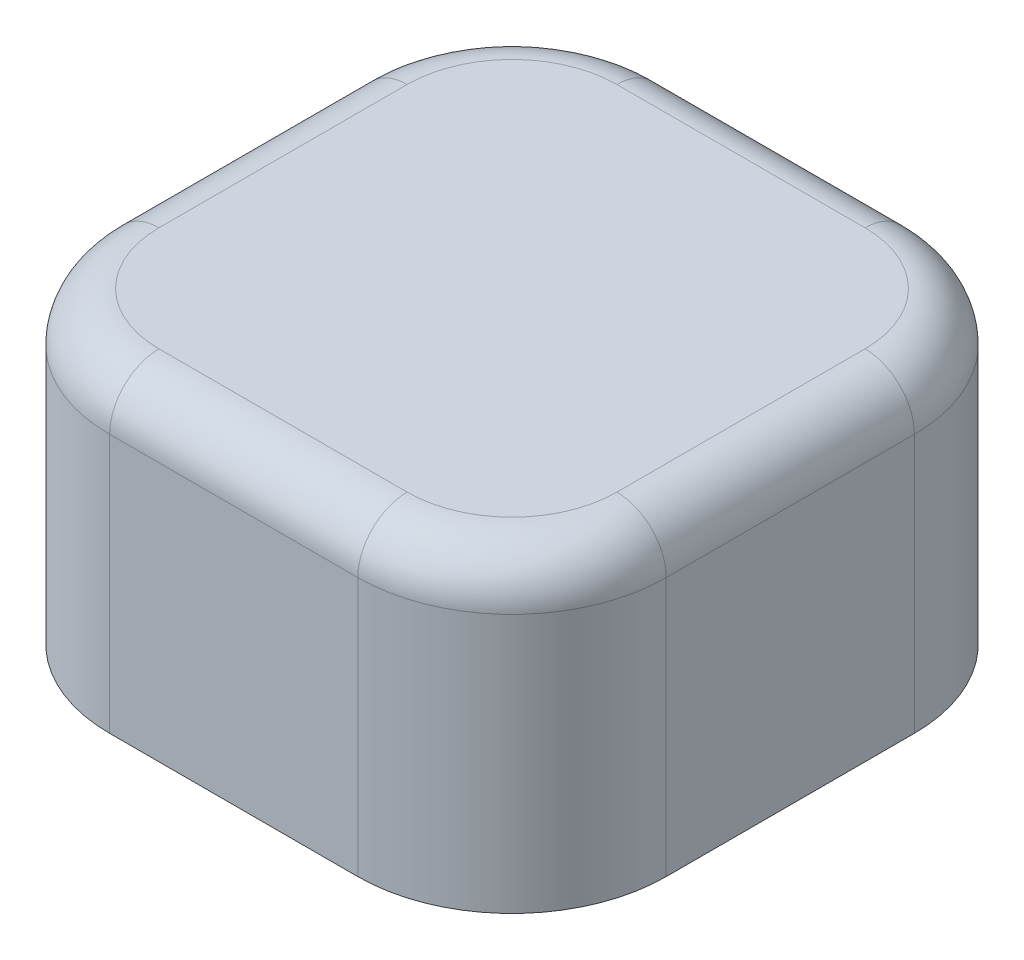
SolidWorks part; units mm, degrees
ref_plane "前视基准面" through (0, 0, 0) normal (0, 0, 1) x (1, 0, 0)
ref_plane "上视基准面" through (0, 0, 0) normal (0, 1, 0) x (1, 0, 0)
ref_plane "右视基准面" through (0, 0, 0) normal (1, 0, 0) x (0, 0, -1)
other "Configuration Table"
sketch "草图1" plane through (0, 0, 0) normal (0, 1, 0) x (1, 0, 0)
  line L0 (-2.2, 0) -> (2.2, 0) construction
  line L1 (0, 2.2) -> (0, -2.2) construction
  line L2 (2.2, 0.6) -> (2.2, -0.6)
  line L3 (-0.6, 2.2) -> (0.6, 2.2)
  line L4 (-2.2, -0.6) -> (-2.2, 0.6)
  line L5 (-0.6, -2.2) -> (0.6, -2.2)
  line L6 (-0.6, 2.2) -> (-0.6, 0.6)
  line L7 (-0.6, 0.6) -> (-2.2, 0.6)
  line L8 (-2.2, -0.6) -> (-0.6, -0.6)
  line L9 (-0.6, -0.6) -> (-0.6, -2.2)
  line L10 (0.6, -2.2) -> (0.6, -0.6)
  line L11 (0.6, -0.6) -> (2.2, -0.6)
  line L12 (2.2, 0.6) -> (0.6, 0.6)
  line L13 (0.6, 0.6) -> (0.6, 2.2)
  circle A0 centre (0, 0) radius 2.8
  point P4 (0, 0)
  point P7 (0, 0)
  point P10 (2.2, 0)
  point P13 (0, 2.2)
  point P16 (-2.2, 0)
  point P19 (0, -2.2)
  dimension "D7" = 5.6
  dimension "D1" = 4.4
  dimension "D2" = 4.4
  dimension "D3" = 1.2
  dimension "D4" = 1.2
  dimension "D5" = 1.2
  dimension "D6" = 1.2
extrude "凸台-拉伸1" add sketch "草图1" against normal blind 8
sketch "草图2" plane through (0, 0, 0) normal (0, 1, 0) x (1, 0, 0)
  line L0 (0, -9.025) -> (0, 9.025) construction
  line L1 (-9.025, 9.025) -> (9.025, 9.025)
  line L2 (-9.025, -9.025) -> (9.025, -9.025)
  line L3 (-9.025, 9.025) -> (-9.025, -9.025)
  line L4 (9.025, 9.025) -> (9.025, -9.025)
  point P4 (0, 0)
  point P8 (0, 9.025)
  point P11 (0, -9.025)
  dimension "D1" = 18.05
  dimension "D2" = 18.05
extrude "凸台-拉伸2" add sketch "草图2" along normal blind 1
sketch "草图3" plane through (0, 0, 0) normal (0, 1, 0) x (1, 0, 0)
  line L4 (9.025, -9.025) -> (9.025, 9.025)
  line L5 (-9.025, -9.025) -> (9.025, -9.025)
  line L6 (-9.025, 9.025) -> (-9.025, -9.025)
  line L7 (9.025, 9.025) -> (-9.025, 9.025)
  line L8 (9.025, -9.025) -> (9.025, 9.025)
  line L9 (-9.025, -9.025) -> (9.025, -9.025)
  line L10 (-9.025, 9.025) -> (-9.025, -9.025)
  line L11 (9.025, 9.025) -> (-9.025, 9.025)
  line L20 (8.025, -8.025) -> (8.025, 8.025)
  line L21 (8.025, 8.025) -> (-8.025, 8.025)
  line L22 (-8.025, 8.025) -> (-8.025, -8.025)
  line L23 (-8.025, -8.025) -> (8.025, -8.025)
  line L24 (8.025, -8.025) -> (8.025, 8.025)
  line L25 (8.025, 8.025) -> (-8.025, 8.025)
  line L26 (-8.025, 8.025) -> (-8.025, -8.025)
  line L27 (-8.025, -8.025) -> (8.025, -8.025)
  dimension "D1" = 0
  dimension "D2" = 1
extrude "凸台-拉伸3" add sketch "草图3" against normal blind 9
sketch "草图6" plane through (0, 0, 0) normal (0, 1, 0) x (1, 0, 0)
  line L0 (0.6, 2.2) -> (-0.6, 2.2) construction
  line L2 (2.2, -0.6) -> (2.2, 0.6) construction
  line L36 (-0.6, -2.2) -> (0.6, -2.2) construction
  line L37 (-2.2, 0.6) -> (-2.2, -0.6) construction
  line L38 (0.6, 2.2) -> (-0.6, 2.2)
  line L39 (2.2, -0.6) -> (2.2, 0.6)
  line L40 (-0.6, -2.2) -> (0.6, -2.2)
  line L41 (-2.2, 0.6) -> (-2.2, -0.6)
  line L42 (-2.2, -0.6) -> (-8.025, -0.6)
  line L43 (-8.025, 8.025) -> (-8.025, -8.025) construction
  line L44 (-8.025, -0.6) -> (-8.025, 0.6)
  line L45 (-8.025, 0.6) -> (-2.2, 0.6)
  line L46 (-0.6, 2.2) -> (-0.6, 8.025)
  line L47 (8.025, 8.025) -> (-8.025, 8.025) construction
  line L48 (-0.6, 8.025) -> (0.6, 8.025)
  line L49 (0.6, 8.025) -> (0.6, 2.2)
  line L50 (2.2, 0.6) -> (8.025, 0.6)
  line L51 (8.025, -8.025) -> (8.025, 8.025) construction
  line L52 (8.025, 0.6) -> (8.025, -0.6)
  line L53 (8.025, -0.6) -> (2.2, -0.6)
  line L54 (0.6, -2.2) -> (0.6, -8.025)
  line L55 (-8.025, -8.025) -> (8.025, -8.025) construction
  line L56 (0.6, -8.025) -> (-0.6, -8.025)
  line L57 (-8.025, -8.025) -> (8.025, -8.025) construction
  line L58 (-0.6, -8.025) -> (-0.6, -2.2)
  point P7 (0, 0)
  point P13 (0, 0)
extrude "凸台-拉伸4" add sketch "草图6" against normal blind 2.5
fillet "圆角3" radius 5 8 edges at (8.025, -4.5, 8.025) (-8.025, -4.5, 8.025) (-8.025, -4.5, -8.025) (8.025, -4.5, -8.025) (-9.025, -4, 9.025) (9.025, -4, 9.025) (9.025, -4, -9.025) (-9.025, -4, -9.025)
fillet "圆角4" radius 1.6 20 edges at (-7.5605, 1, -7.5605) (0, 1, -9.025) (7.5605, 1, -7.5605) (9.025, 1, 0) (7.5605, 1, 7.5605) (0, 1, 9.025) (-7.5605, 1, 7.5605) (-9.025, 1, 0) (-8.025, 0, -1.8125) (-1.8125, 0, -8.025) (1.8125, 0, -8.025) (8.025, 0, -1.8125) (8.025, 0, 1.8125) (1.8125, 0, 8.025) (-1.8125, 0, 8.025) (-8.025, 0, 1.8125) (-6.5605, 0, -6.5605) (6.5605, 0, -6.5605) (6.5605, 0, 6.5605) (-6.5605, 0, 6.5605)
